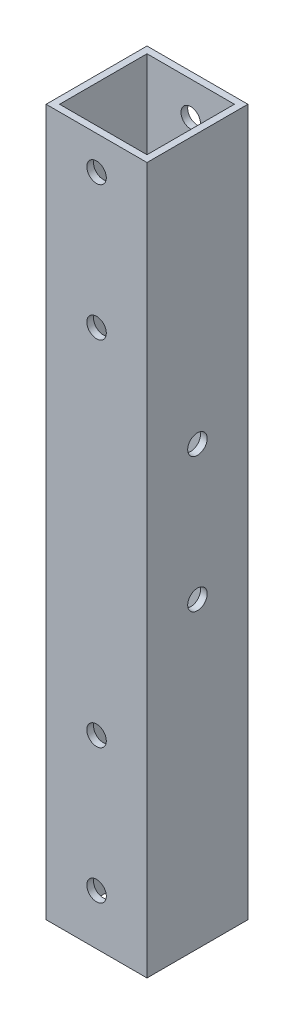
SolidWorks part; units mm, degrees
material "Thornel Mat VMA"
ref_plane "前视基准面" through (0, 0, 0) normal (0, 0, 1) x (1, 0, 0)
ref_plane "上视基准面" through (0, 0, 0) normal (0, 1, 0) x (1, 0, 0)
ref_plane "右视基准面" through (0, 0, 0) normal (1, 0, 0) x (0, 0, -1)
sketch "草图1" plane through (0, 0, 0) normal (0, 1, 0) x (1, 0, 0)
  line L1 (-7.5, -7.5) -> (7.5, -7.5)
  line L2 (-7.5, -7.5) -> (-7.5, 7.5)
  line L3 (-7.5, 7.5) -> (7.5, 7.5)
  line L4 (7.5, -7.5) -> (7.5, 7.5)
  line L5 (-7.5, -7.5) -> (7.5, 7.5) construction
  line L6 (-7.5, 7.5) -> (7.5, -7.5) construction
  point P0 (0, 0)
  dimension "D1" = 15
  dimension "D2" = 15
extrude "拉伸-薄壁1" add sketch "草图1" along normal blind 105 thin thin type one direction reverse wall 1
sketch "草图2" plane through (0, 0, 7.5) normal (0, 0, 1) x (1, 0, 0)
  line L0 (0, 0) -> (0, 105) construction
  line L1 (-7.5, 105) -> (7.5, 105) construction
  line L2 (-7.5, 0) -> (7.5, 0) construction
  circle A0 centre (0, 7.5) radius 1.45
  circle A1 centre (0, 27.5) radius 1.45
  circle A2 centre (0, 100) radius 1.45
  circle A3 centre (0, 80) radius 1.45
  dimension "D1" = 2.9
  dimension "D4" = 5
  dimension "D5" = 20
  dimension "D2" = 7.5
  dimension "D3" = 20
extrude "切除-拉伸1" cut sketch "草图2" against normal through all
sketch "草图3" plane through (7.5, 0, 0) normal (1, 0, 0) x (0, 0, -1)
  line L0 (0, 0) -> (0, 105) construction
  line L1 (-7.5, 105) -> (7.5, 105) construction
  circle A0 centre (0, 65) radius 1.45
  circle A1 centre (0, 45) radius 1.45
  dimension "D1" = 2.9
  dimension "D2" = 40
  dimension "D3" = 20
extrude "切除-拉伸2" cut sketch "草图3" against normal through all
